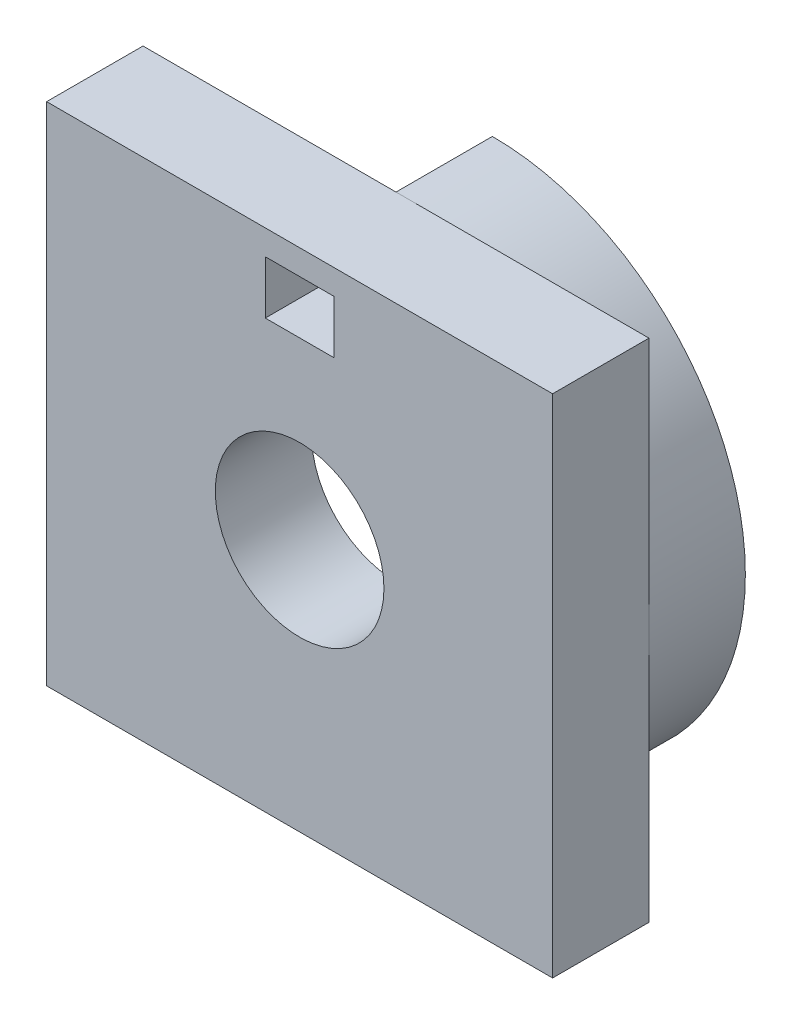
SolidWorks part; units mm, degrees
ref_plane "Front Plane" through (0, 0, 0) normal (0, 0, 1) x (1, 0, 0)
ref_plane "Top Plane" through (0, 0, 0) normal (0, 1, 0) x (1, 0, 0)
ref_plane "Right Plane" through (0, 0, 0) normal (1, 0, 0) x (0, 0, -1)
sketch "Sketch1" plane through (0, 0, 0) normal (0, 0, 1) x (1, 0, 0)
  line L1 (-10.5, 10.5) -> (10.5, 10.5)
  line L2 (-10.5, 10.5) -> (-10.5, -10.5)
  line L3 (-10.5, -10.5) -> (10.5, -10.5)
  line L4 (10.5, 10.5) -> (10.5, -10.5)
  line L5 (0, -10.5) -> (0, 10.5) construction
  line L6 (-10.5, 0) -> (10.5, 0) construction
  circle A0 centre (0, 0) radius 3.5
  dimension "D1" = 7
  dimension "D2" = 21
  dimension "D3" = 21
extrude "Boss-Extrude1" add sketch "Sketch1" along normal blind 4
sketch "Sketch2" plane through (0, 0, 0) normal (0, 0, -1) x (-1, 0, 0)
  line L0 (0, 10.5) -> (0, 9)
  line L1 (0, -9) -> (0, -10.5)
  arc A0 (0, 9) -> (0, -9) centre (0, 0) ccw
  arc A1 (0, 10.5) -> (0, -10.5) centre (0, 0) ccw
  dimension "D1" = 9
  dimension "D2" = 1.5
extrude "Boss-Extrude2" add sketch "Sketch2" along normal blind 4
sketch "Sketch3" plane through (0, 0, 0) normal (0, 0, -1) x (-1, 0, 0)
  line L0 (0, 0) -> (0, 9.4638) construction
  line L1 (-1.425, 9.4638) -> (1.425, 9.4638)
  line L2 (-1.425, 9.4638) -> (-1.425, 7.2584)
  line L3 (-1.425, 7.2584) -> (1.425, 7.2584)
  line L4 (1.425, 9.4638) -> (1.425, 7.2584)
  line L5 (0, 7.2584) -> (0, 9.4638) construction
  line L6 (-1.425, 8.3611) -> (1.425, 8.3611) construction
  point P284 (0, 8.3611)
  dimension "D1" = 2.85
extrude "Cut-Extrude1" cut sketch "Sketch3" against normal blind 4
